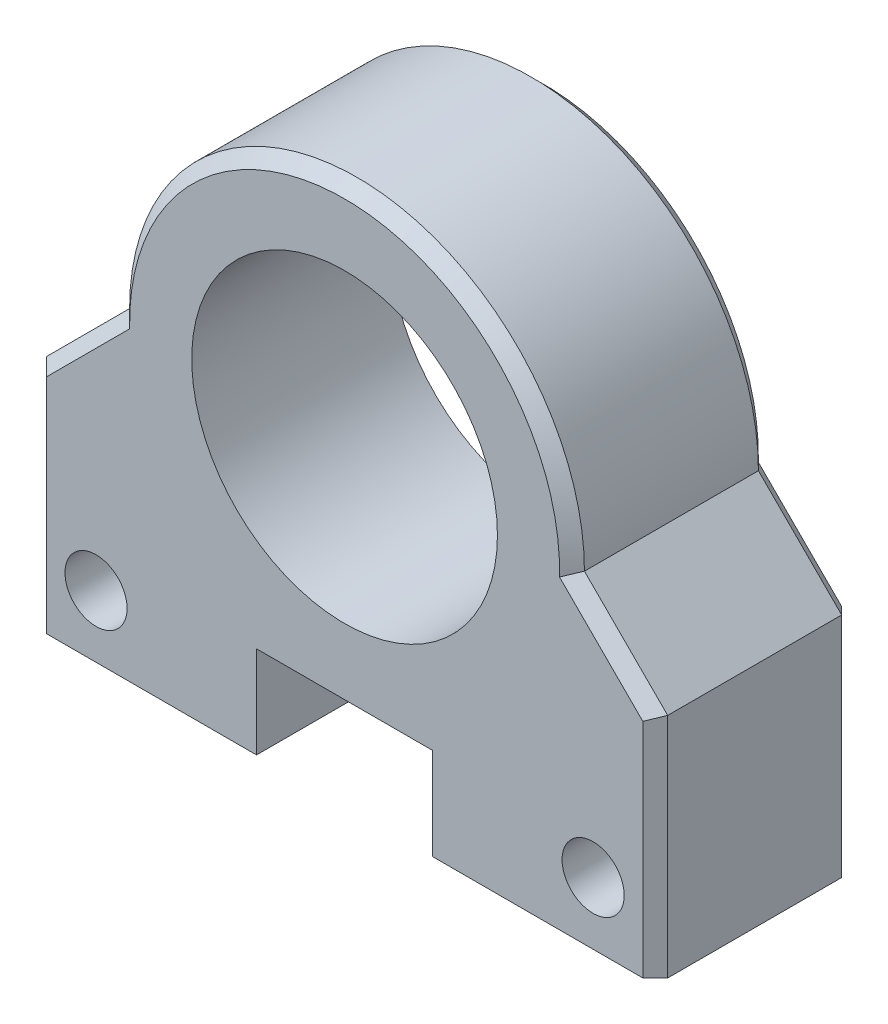
SolidWorks part; units mm, degrees
ref_plane "Front Plane" through (0, 0, 0) normal (0, 0, 1) x (1, 0, 0)
ref_plane "Top Plane" through (0, 0, 0) normal (0, 1, 0) x (1, 0, 0)
ref_plane "Right Plane" through (0, 0, 0) normal (1, 0, 0) x (0, 0, -1)
sketch "Sketch1" plane through (0, 0, 0) normal (0, 0, 1) x (1, 0, 0)
  line L0 (0, -26.1041) -> (0, 52.7781) construction
  line L1 (4.5, 4.699) -> (-4.5, 4.699)
  line L2 (-4.5, 4.699) -> (-4.5, 0)
  line L3 (-4.5, 0) -> (-15.875, 0)
  line L4 (15.875, 0) -> (15.875, 11.6205)
  line L5 (15.875, 11.6205) -> (11.6205, 15.875)
  line L6 (4.5, 4.699) -> (4.5, 0)
  line L7 (-15.875, 0) -> (-15.875, 11.6205)
  line L8 (4.5, 0) -> (15.875, 0)
  line L9 (-15.875, 11.6205) -> (-11.6205, 15.875)
  circle A0 centre (0, 15.875) radius 7.8105
  arc A1 (-11.6205, 15.875) -> (11.6205, 15.875) centre (0, 15.875) cw
  point P11 (0, 4.699)
  point P12 (0, 28.448)
  point P15 (0, 8.0645)
  dimension "D6" = 15.621
  dimension "D3" = 3.81
  dimension "D1" = 9
  dimension "D2" = 4.699
  dimension "D4" = 45
  dimension "D5" = 15.875
  dimension "D7" = 31.75
extrude "Boss-Extrude1" add sketch "Sketch1" along normal blind 10.16
chamfer "Chamfer2" distance 0.635 angle 45 10 edges at (15.875, 5.8103, 0) (13.7477, 13.7478, 0) (-15.875, 5.8103, 0) (-13.7477, 13.7478, 0) (0, 27.4955, 0) (15.875, 5.8103, 10.16) (13.7477, 13.7478, 10.16) (-15.875, 5.8103, 10.16) (-13.7477, 13.7478, 10.16) (0, 27.4955, 10.16)
sketch "Sketch2" plane through (0, 0, 10.16) normal (0, 0, 1) x (1, 0, 0)
  line L0 (0, 0) -> (0, 48.3533) construction
  line L1 (-15.24, 0) -> (-4.5, 0) construction
  line L3 (-15.875, 0) -> (-15.875, 11.6205) construction
  circle A0 centre (-12.7, 3.175) radius 1.5875
  circle A1 centre (12.7, 3.175) radius 1.5875
  dimension "D1" = 3.175
  dimension "D2" = 3.175
  dimension "D3" = 3.175
extrude "Cut-Extrude1" cut sketch "Sketch2" against normal through all
